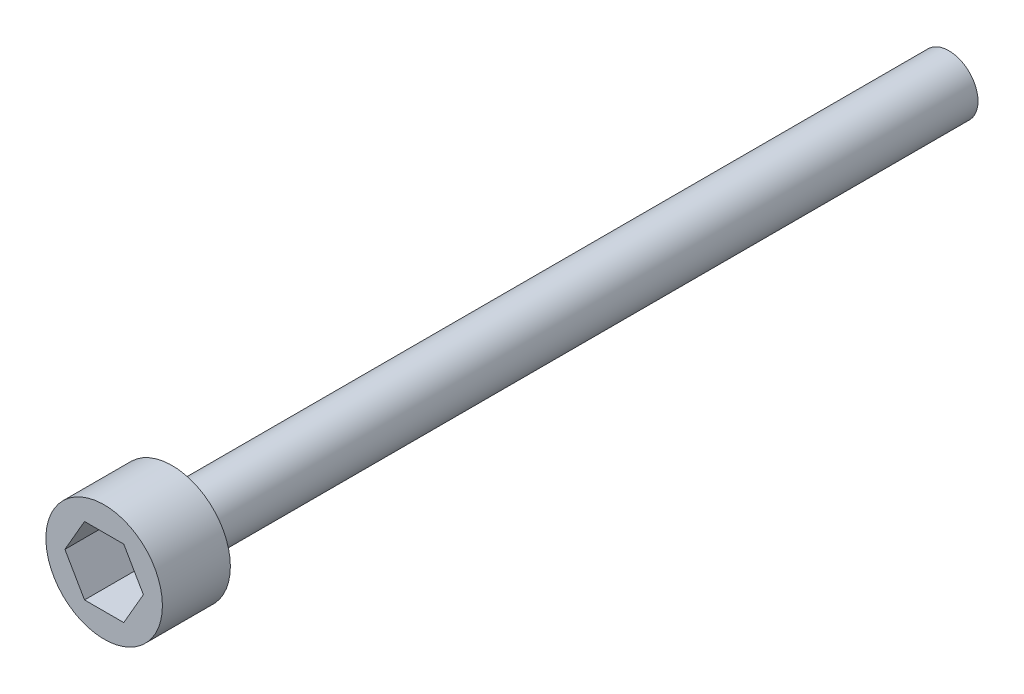
SolidWorks part; units mm, degrees
material "Alloy Steel"
ref_plane "Front Plane" through (0, 0, 0) normal (0, 0, 1) x (1, 0, 0)
ref_plane "Top Plane" through (0, 0, 0) normal (0, 1, 0) x (1, 0, 0)
ref_plane "Right Plane" through (0, 0, 0) normal (1, 0, 0) x (0, 0, -1)
sketch "Sketch1" plane through (0, 0, 0) normal (0, 0, 1) x (1, 0, 0)
  circle A0 centre (0, 0) radius 3
  dimension "D1" = 6
extrude "Head Boss-Extrude1" add sketch "Sketch1" along normal blind 3.5
sketch "Sketch3" plane through (0, 0, 3.5) normal (0, 0, 1) x (1, 0, 0)
  line L0 (-1.0104, 1.75) -> (1.0104, 1.75)
  line L1 (1.0104, 1.75) -> (2.0207, 0)
  line L2 (2.0207, 0) -> (1.0104, -1.75)
  line L3 (1.0104, -1.75) -> (-1.0104, -1.75)
  line L4 (-1.0104, -1.75) -> (-2.0207, 0)
  line L5 (-2.0207, 0) -> (-1.0104, 1.75)
  line L6 (-2.0207, 0) -> (0, 0) construction
  line L7 (2.0207, 0) -> (0, 0) construction
  line L8 (-1.0104, -1.75) -> (0, 0) construction
  line L9 (0, 0) -> (1.0104, 1.75) construction
  line L10 (-1.0104, 1.75) -> (0, 0) construction
  line L11 (0, 0) -> (1.0104, -1.75) construction
  dimension "D1" = 60
  dimension "D2" = 60
  dimension "D3" = 60
  dimension "D4" = 60
  dimension "D5" = 60
  dimension "D6" = 3.5
extrude "Head Hex Cut-Extrude1" cut sketch "Sketch3" against normal blind 2.8
sketch "Sketch2" plane through (0, 0, 0) normal (0, 0, 1) x (1, 0, 0)
  circle A0 centre (0, 0) radius 1.5
  dimension "D1" = 3
extrude "Screw Boss-Extrude2" add sketch "Sketch2" against normal blind 40
